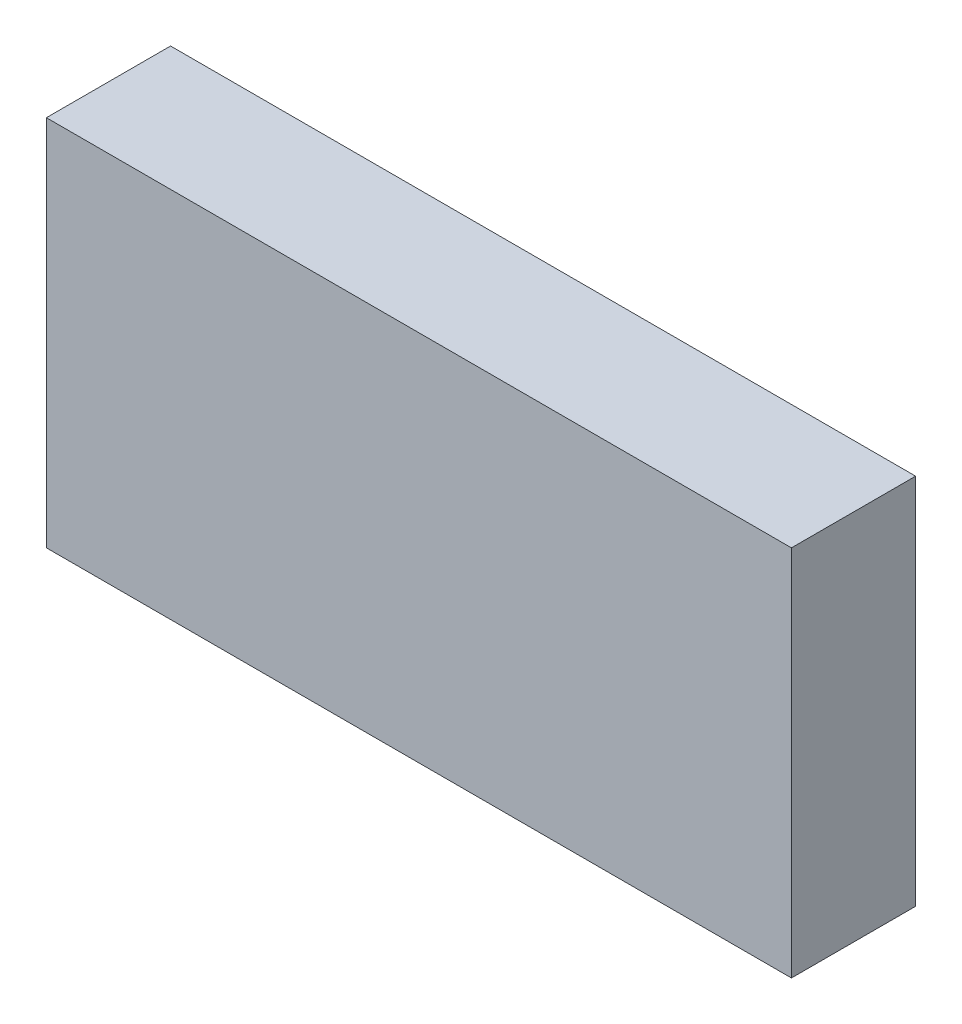
SolidWorks part; units mm, degrees
material "ABS"
ref_plane "Front" through (0, 0, 0) normal (0, 0, 1) x (1, 0, 0)
ref_plane "Top" through (0, 0, 0) normal (0, 1, 0) x (1, 0, 0)
ref_plane "Right" through (0, 0, 0) normal (1, 0, 0) x (0, 0, -1)
sketch "Sketch1" plane through (0, 0, 0) normal (0, 0, 1) x (1, 0, 0)
  line L1 (-45, -22.5) -> (45, -22.5)
  line L2 (-45, -22.5) -> (-45, 22.5)
  line L3 (-45, 22.5) -> (45, 22.5)
  line L4 (45, -22.5) -> (45, 22.5)
  line L5 (-45, -22.5) -> (45, 22.5) construction
  line L6 (-45, 22.5) -> (45, -22.5) construction
  point P0 (0, 0)
extrude "Boss-Extrude1" add sketch "Sketch1" along normal blind 15
